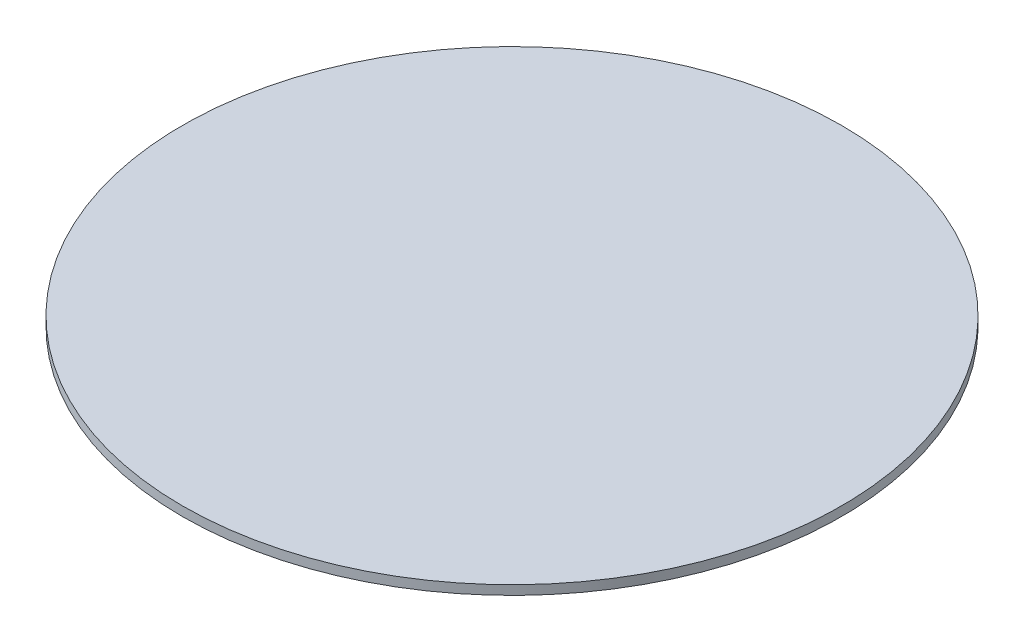
SolidWorks part; units mm, degrees
ref_plane "前基準面" through (0, 0, 0) normal (0, 0, 1) x (1, 0, 0)
ref_plane "上基準面" through (0, 0, 0) normal (0, 1, 0) x (1, 0, 0)
ref_plane "右基準面" through (0, 0, 0) normal (1, 0, 0) x (0, 0, -1)
sketch "草圖1" plane through (0, 0, 0) normal (0, 1, 0) x (1, 0, 0)
  circle A0 centre (0, 0) radius 71
  dimension "D1" = 142
extrude "填料-伸長1" add sketch "草圖1" along normal blind 2
sketch "草圖2" plane through (0, 2, 0) normal (0, 1, 0) x (1, 0, 0)
  line L1 (-34, 34) -> (34, 34)
  line L2 (-34, 34) -> (-34, -34)
  line L3 (-34, -34) -> (34, -34)
  line L4 (34, 34) -> (34, -34)
  line L5 (-34, 34) -> (34, -34) construction
  line L6 (-34, -34) -> (34, 34) construction
  point P0 (0, 0)
  point P9 (-30, 30)
  point P10 (30, 30)
  point P11 (30, -30)
  point P12 (-30, -30)
  point P13 (0, 0)
  dimension "D1" = 68
  dimension "D2" = 4
  dimension "D3" = 4
